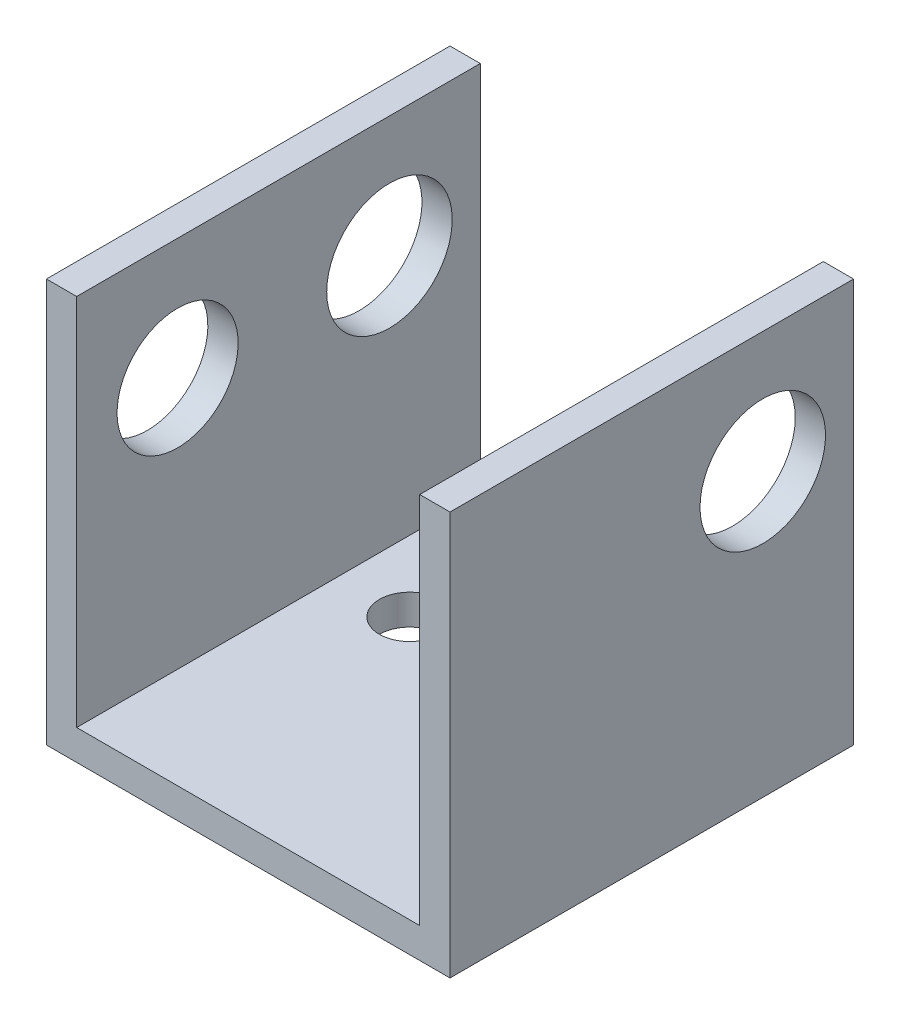
SolidWorks part; units mm, degrees
ref_plane "Plan de face" through (0, 0, 0) normal (0, 0, 1) x (1, 0, 0)
ref_plane "Plan de dessus" through (0, 0, 0) normal (0, 1, 0) x (1, 0, 0)
ref_plane "Plan de droite" through (0, 0, 0) normal (1, 0, 0) x (0, 0, -1)
sketch "Esquisse1" plane through (0, 0, 0) normal (0, 0, 1) x (1, 0, 0)
  line L0 (-31.1486, 3.3838) -> (-29.6486, 3.3838)
  line L1 (-29.6486, 3.3838) -> (-29.6486, -15.1162)
  line L2 (-29.6486, -15.1162) -> (-12.6486, -15.1162)
  line L3 (-11.1486, 3.3838) -> (-11.1486, -16.6162)
  line L4 (-11.1486, -16.6162) -> (-31.1486, -16.6162)
  line L5 (-31.1486, -16.6162) -> (-31.1486, 3.3838)
  line L6 (-12.6486, -15.1162) -> (-12.6486, 3.3838)
  line L7 (-12.6486, 3.3838) -> (-11.1486, 3.3838)
  dimension "D1" = 20
  dimension "D2" = 1.5
  dimension "D3" = 1.5
  dimension "D4" = 20
  dimension "D5" = 1.5
  dimension "D6" = 20
extrude "Extrusion1" add sketch "Esquisse1" along normal blind 20
sketch "Esquisse2" plane through (0, -15.1162, 0) normal (0, 1, 0) x (-1, 0, 0)
  line L0 (12.6486, 0) -> (29.6486, 0) construction
  line L1 (31.1486, 20) -> (31.1486, 0) construction
  line L3 (12.6486, 20) -> (29.6486, 20) construction
  line L5 (11.1486, 20) -> (11.1486, 0) construction
  circle A0 centre (26.1486, 7) radius 1.5
  circle A2 centre (16.1486, 13) radius 1.5
  dimension "D4" = 7
  dimension "D1" = 5
  dimension "D2" = 5
  dimension "D3" = 7
extrude "Extrusion2" cut sketch "Esquisse2" against normal through all
sketch "Esquisse4" plane through (-29.6486, 0, 0) normal (1, 0, 0) x (0, 0, -1)
  line L0 (-20, -15.1162) -> (-20, 3.3838) construction
  line L4 (-20, 3.3838) -> (0, 3.3838) construction
  circle A1 centre (-15, -2.6162) radius 3
  dimension "D3" = 6
  dimension "D4" = 5
extrude "Extrusion3" cut sketch "Esquisse4" against normal through all
sketch "Esquisse6" plane through (-31.1486, 0, 0) normal (-1, 0, 0) x (0, 0, 1)
  line L0 (0, 3.3838) -> (0, -16.6162) construction
  line L1 (20, 3.3838) -> (0, 3.3838) construction
  circle A0 centre (4.5, -2.6162) radius 3.11
  dimension "D1" = 4.5
  dimension "D2" = 6
extrude "Extrusion4" cut sketch "Esquisse6" against normal through all
